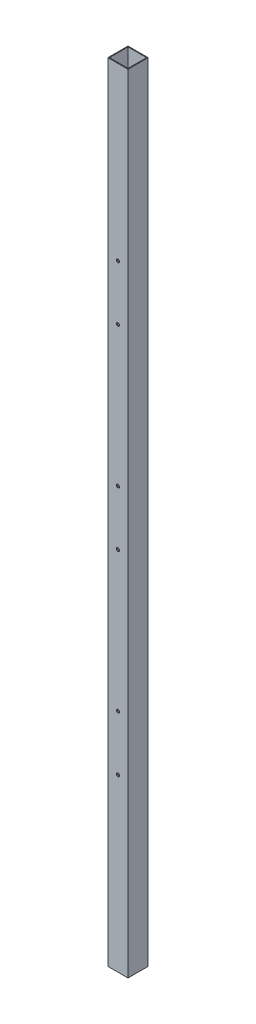
SolidWorks part; units mm, degrees
ref_plane "Front Plane" through (0, 0, 0) normal (0, 0, 1) x (1, 0, 0)
ref_plane "Top Plane" through (0, 0, 0) normal (0, 1, 0) x (1, 0, 0)
ref_plane "Right Plane" through (0, 0, 0) normal (1, 0, 0) x (0, 0, -1)
sketch "Sketch1" plane through (0, 0, 0) normal (0, 1, 0) x (1, 0, 0)
  line L0 (-11.8, 11.8) -> (11.8, 11.8)
  line L1 (-12.8, 12.8) -> (12.8, 12.8)
  line L2 (-12.8, 12.8) -> (-12.8, -12.8)
  line L3 (-12.8, -12.8) -> (12.8, -12.8)
  line L4 (12.8, 12.8) -> (12.8, -12.8)
  line L5 (-12.8, 12.8) -> (12.8, -12.8) construction
  line L6 (-12.8, -12.8) -> (12.8, 12.8) construction
  line L7 (11.8, 11.8) -> (11.8, -11.8)
  line L8 (-11.8, -11.8) -> (11.8, -11.8)
  line L9 (-11.8, 11.8) -> (-11.8, -11.8)
  point P0 (0, 0)
  dimension "D1" = 25.6
  dimension "D2" = 25.6
  dimension "D3" = 1
extrude "Boss-Extrude1" add sketch "Sketch1" along normal blind 1000
sketch "Sketch2" plane through (0, 0, -12.8) normal (0, 0, -1) x (-1, 0, 0)
  line L0 (-12.8, 500) -> (12.8, 500) construction
  line L1 (-12.8, 1000) -> (-12.8, 0) construction
  line L2 (12.8, 1000) -> (12.8, 0) construction
  line L3 (0, 500) -> (0, 450) construction
  line L4 (0, 500) -> (0, 550) construction
  line L5 (0, 550) -> (0, 945.6) construction
  line L6 (17.8, 945.6) -> (-17.8, 945.6) construction
  line L7 (0, 450) -> (0, 54.4) construction
  line L8 (17.8, 54.4) -> (-17.8, 54.4) construction
  line L9 (0, 747.8) -> (0, 712.8) construction
  line L10 (0, 747.8) -> (0, 782.8) construction
  line L11 (0, 252.2) -> (0, 208.1396) construction
  line L12 (0, 252.2) -> (0, 297.4217) construction
  circle A0 centre (0, 535) radius 2
  circle A1 centre (0, 465) radius 2
  circle A2 centre (0, 782.8) radius 2
  circle A3 centre (0, 712.8) radius 2
  circle A4 centre (0, 287.2) radius 2
  circle A5 centre (0, 217.2) radius 2
  dimension "D3" = 4
  dimension "D8" = 4
  dimension "D1" = 50
  dimension "D2" = 50
  dimension "D4" = 15
  dimension "D5" = 15
  dimension "D6" = 35
  dimension "D7" = 35
extrude "Cut-Extrude1" cut sketch "Sketch2" against normal blind 33
